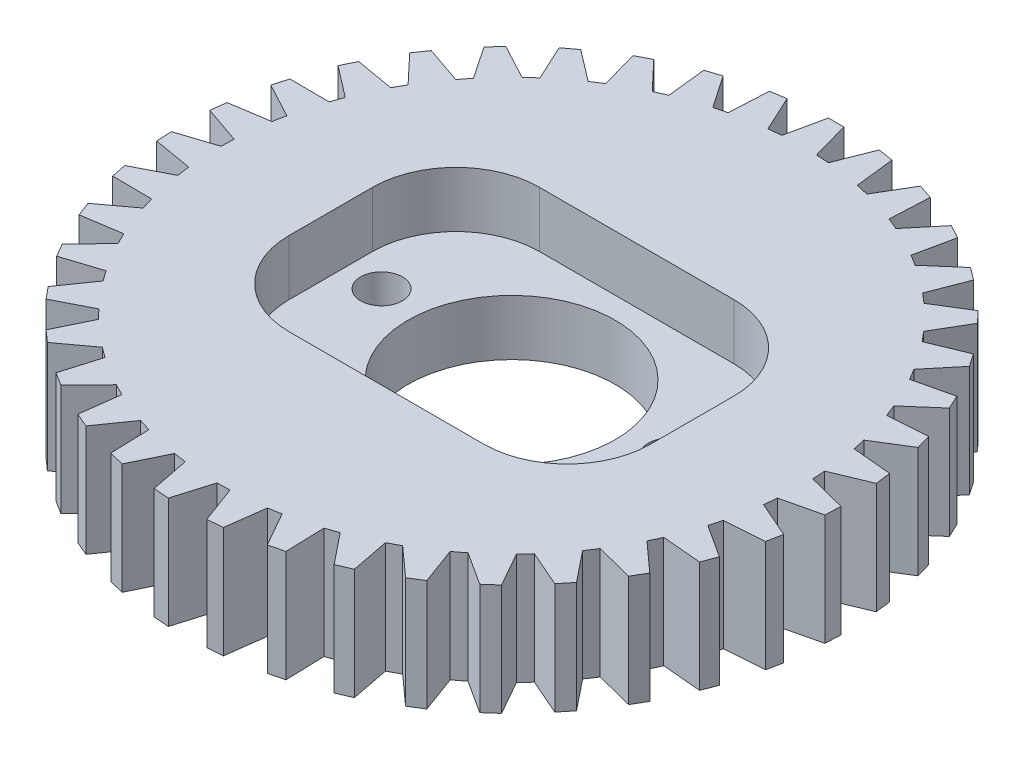
SolidWorks part; units mm, degrees
ref_plane "Front Plane" through (0, 0, 0) normal (0, 0, 1) x (1, 0, 0)
ref_plane "Top Plane" through (0, 0, 0) normal (0, 1, 0) x (1, 0, 0)
ref_plane "Right Plane" through (0, 0, 0) normal (1, 0, 0) x (0, 0, -1)
sketch "Sketch2" plane through (0, 0, 0) normal (0, 1, 0) x (1, 0, 0)
  line L0 (0, 10.5) -> (0, -22.3339) construction
  line L1 (10.5, 0) -> (-25.2541, 0) construction
  circle A0 centre (0, 0) radius 10.5
  dimension "D1" = 21
extrude "Boss-Extrude1" add sketch "Sketch2" along normal blind 4
sketch "Sketch3" plane through (0, 4, 0) normal (0, 1, 0) x (1, 0, 0)
  line L1 (-6.5, 4.5) -> (6.5, 4.5)
  line L2 (-6.5, 4.5) -> (-6.5, -4.5)
  line L3 (-6.5, -4.5) -> (6.5, -4.5)
  line L4 (6.5, 4.5) -> (6.5, -4.5)
  line L5 (-6.5, 4.5) -> (6.5, -4.5) construction
  line L6 (-6.5, -4.5) -> (6.5, 4.5) construction
  point P0 (0, 0)
  dimension "D1" = 13
  dimension "D2" = 9
extrude "Cut-Extrude1" cut sketch "Sketch3" against normal blind 2
fillet "Fillet1" radius 3 4 edges at (-6.5, 3, 4.5) (6.5, 3, 4.5) (-6.5, 3, -4.5) (6.5, 3, -4.5)
sketch "Sketch4" plane through (0, 2, 0) normal (0, 1, 0) x (1, 0, 0)
  line L1 (3.5, 4.5) -> (-3.5, 4.5) construction
  line L2 (0, 0) -> (0, -17.7909) construction
  circle A0 centre (0, 0) radius 3.725
  circle A2 centre (-5.1761, 0.4977) radius 0.75
  circle A3 centre (5.1761, 0.4977) radius 0.75
  dimension "D1" = 7.45
  dimension "D2" = 5.2
  dimension "D3" = 4.5
extrude "Cut-Extrude2" cut sketch "Sketch4" against normal through all
sketch "Sketch5" plane through (0, 4, 0) normal (0, 1, 0) x (1, 0, 0)
  line L0 (-0.7576, 10.4726) -> (-0.4614, 11.8538)
  line L1 (-0.4614, 11.8538) -> (0.0939, 11.8538)
  line L2 (0.0939, 11.8538) -> (0.4777, 10.4891)
  line L3 (1.9941, 11.6853) -> (2.1541, 10.2767)
  line L4 (1.446, 11.7743) -> (1.9941, 11.6853)
  line L5 (0.9321, 10.4585) -> (1.446, 11.7743)
  line L6 (3.8428, 11.2141) -> (3.7747, 9.798)
  line L7 (3.3161, 11.3899) -> (3.8428, 11.2141)
  line L8 (2.5977, 10.1736) -> (3.3161, 11.3899)
  line L9 (5.5919, 10.4524) -> (5.2976, 9.0656)
  line L10 (5.1002, 10.7105) -> (5.5919, 10.4524)
  line L11 (4.196, 9.6251) -> (5.1002, 10.7105)
  line L12 (7.1961, 9.4201) -> (6.6832, 8.0985)
  line L13 (6.7522, 9.7536) -> (7.1961, 9.4201)
  line L14 (5.6857, 8.8274) -> (6.7522, 9.7536)
  line L15 (8.614, 8.1437) -> (7.8957, 6.9215)
  line L16 (8.2294, 8.5442) -> (8.614, 8.1437)
  line L17 (7.0281, 7.801) -> (8.2294, 8.5442)
  line L18 (9.8088, 6.6565) -> (8.9038, 5.5653)
  line L19 (9.4934, 7.1135) -> (9.8088, 6.6565)
  line L20 (8.1884, 6.5726) -> (9.4934, 7.1135)
  line L21 (10.7496, 4.9968) -> (9.6812, 4.065)
  line L22 (10.5115, 5.4985) -> (10.7496, 4.9968)
  line L23 (9.1367, 5.174) -> (10.5115, 5.4985)
  line L24 (11.4119, 3.2078) -> (10.2079, 2.4594)
  line L25 (11.2574, 3.7411) -> (11.4119, 3.2078)
  line L26 (9.8484, 3.6414) -> (11.2574, 3.7411)
  line L27 (11.7787, 1.3356) -> (10.4702, 0.7901)
  line L28 (11.7118, 1.8869) -> (11.7787, 1.3356)
  line L29 (10.305, 2.0144) -> (11.7118, 1.8869)
  line L30 (11.8404, -0.5711) -> (10.4614, -0.8997)
  line L31 (11.8628, -0.0163) -> (11.8404, -0.5711)
  line L32 (10.4946, 0.3353) -> (11.8628, -0.0163)
  line L33 (11.5955, -2.463) -> (10.1816, -2.5662)
  line L34 (11.7066, -1.919) -> (11.5955, -2.463)
  line L35 (10.4125, -1.3525) -> (11.7066, -1.919)
  line L36 (11.0502, -4.2912) -> (9.6381, -4.1662)
  line L37 (11.2471, -3.772) -> (11.0502, -4.2912)
  line L38 (10.0607, -3.0053) -> (11.2471, -3.772)
  line L39 (10.2188, -6.0082) -> (8.845, -5.6583)
  line L40 (10.4964, -5.5273) -> (10.2188, -6.0082)
  line L41 (9.4484, -4.5802) -> (10.4964, -5.5273)
  line L42 (9.1227, -7.5696) -> (7.8228, -7.0039)
  line L43 (9.4738, -7.1395) -> (9.1227, -7.5696)
  line L44 (8.5913, -6.0365) -> (9.4738, -7.1395)
  line L45 (7.7903, -8.935) -> (6.598, -8.168)
  line L46 (8.2059, -8.5667) -> (7.7903, -8.935)
  line L47 (7.5117, -7.3365) -> (8.2059, -8.5667)
  line L48 (6.2561, -10.0689) -> (5.2023, -9.1206)
  line L49 (6.7254, -9.7721) -> (6.2561, -10.0689)
  line L50 (6.2376, -8.4464) -> (6.7254, -9.7721)
  line L51 (4.5599, -10.9421) -> (3.6719, -9.837)
  line L52 (5.0708, -10.7244) -> (4.5599, -10.9421)
  line L53 (4.8019, -9.3376) -> (5.0708, -10.7244)
  line L54 (2.7457, -11.5318) -> (2.0464, -10.2987)
  line L55 (3.2848, -11.3989) -> (2.7457, -11.5318)
  line L56 (3.2419, -9.987) -> (3.2848, -11.3989)
  line L57 (0.8603, -11.8229) -> (0.3678, -10.4936)
  line L58 (1.4138, -11.7782) -> (0.8603, -11.8229)
  line L59 (1.5979, -10.3777) -> (1.4138, -11.7782)
  line L60 (-1.0474, -11.8078) -> (-1.3202, -10.4167)
  line L61 (-0.4939, -11.8525) -> (-1.0474, -11.8078)
  line L62 (-0.0875, -10.4996) -> (-0.4939, -11.8525)
  line L63 (-2.9279, -11.4869) -> (-2.9741, -10.07)
  line L64 (-2.3888, -11.6198) -> (-2.9279, -11.4869)
  line L65 (-1.7707, -10.3496) -> (-2.3888, -11.6198)
  line L66 (-4.7327, -10.8685) -> (-4.5509, -9.4625)
  line L67 (-4.2218, -11.0861) -> (-4.7327, -10.8685)
  line L68 (-3.4079, -9.9316) -> (-4.2218, -11.0861)
  line L69 (-6.4148, -9.9686) -> (-6.0099, -8.61)
  line L70 (-5.9455, -10.2653) -> (-6.4148, -9.9686)
  line L71 (-4.9569, -9.2563) -> (-5.9455, -10.2653)
  line L72 (-7.9308, -8.8105) -> (-7.3132, -7.5344)
  line L73 (-7.5152, -9.1787) -> (-7.9308, -8.8105)
  line L74 (-6.3775, -8.3413) -> (-7.5152, -9.1787)
  line L75 (-9.2414, -7.4242) -> (-8.4271, -6.2637)
  line L76 (-8.8902, -7.8543) -> (-9.2414, -7.4242)
  line L77 (-7.633, -7.2102) -> (-8.8902, -7.8543)
  line L78 (-10.3126, -5.8456) -> (-9.3227, -4.8308)
  line L79 (-10.035, -6.3265) -> (-10.3126, -5.8456)
  line L80 (-8.6908, -5.8924) -> (-10.035, -6.3265)
  line L81 (-11.1168, -4.1157) -> (-9.9769, -3.2728)
  line L82 (-10.9199, -4.6349) -> (-11.1168, -4.1157)
  line L83 (-9.5234, -4.422) -> (-10.9199, -4.6349)
  line L84 (-11.633, -2.2791) -> (-10.3727, -1.63)
  line L85 (-11.522, -2.8232) -> (-11.633, -2.2791)
  line L86 (-10.1094, -2.8371) -> (-11.522, -2.8232)
  line L87 (-11.848, -0.3835) -> (-10.4999, 0.055)
  line L88 (-11.8256, -0.9383) -> (-11.848, -0.3835)
  line L89 (-10.4336, -1.1787) -> (-11.8256, -0.9383)
  line L90 (-11.7561, 1.522) -> (-10.3551, 1.7386)
  line L91 (-11.823, 0.9708) -> (-11.7561, 1.522)
  line L92 (-10.4876, 0.5102) -> (-11.823, 0.9708)
  line L93 (-11.3597, 3.3881) -> (-9.9421, 3.3771)
  line L94 (-11.5142, 2.8547) -> (-11.3597, 3.3881)
  line L95 (-10.2699, 2.186) -> (-11.5142, 2.8547)
  line L96 (-10.6691, 5.1664) -> (-9.2716, 4.9282)
  line L97 (-10.9071, 4.6648) -> (-10.6691, 5.1664)
  line L98 (-9.7863, 3.8051) -> (-10.9071, 4.6648)
  line L99 (-9.7022, 6.811) -> (-8.361, 6.3517)
  line L100 (-10.0176, 6.354) -> (-9.7022, 6.811)
  line L101 (-9.0492, 5.3256) -> (-10.0176, 6.354)
  line L102 (-8.484, 8.2791) -> (-7.2338, 7.6106)
  line L103 (-8.8686, 7.8787) -> (-8.484, 8.2791)
  line L104 (-8.0777, 6.7082) -> (-8.8686, 7.8787)
  line L105 (-7.0461, 9.5328) -> (-5.9193, 8.6725)
  line L106 (-7.49, 9.1993) -> (-7.0461, 9.5328)
  line L107 (-6.897, 7.9171) -> (-7.49, 9.1993)
  line L108 (-5.4256, 10.5397) -> (-4.4515, 9.5097)
  line L109 (-5.9173, 10.2816) -> (-5.4256, 10.5397)
  line L110 (-5.5377, 8.921) -> (-5.9173, 10.2816)
  line L111 (-3.6647, 11.2735) -> (-2.8684, 10.1006)
  line L112 (-4.1914, 11.0977) -> (-3.6647, 11.2735)
  line L113 (-4.035, 9.6938) -> (-4.1914, 11.0977)
  line L114 (-1.8088, 11.7154) -> (-1.211, 10.4299)
  line L115 (-2.3569, 11.6263) -> (-1.8088, 11.7154)
  line L116 (-2.4277, 10.2155) -> (-2.3569, 11.6263)
  circle A0 centre (0, 0) radius 10.5 construction
  arc A1 (-0.7576, 10.4726) -> (0.4777, 10.4891) centre (0, 0) cw
  arc A2 (0.9321, 10.4585) -> (2.1541, 10.2767) centre (0, 0) cw
  arc A3 (2.5977, 10.1736) -> (3.7747, 9.798) centre (0, 0) cw
  arc A4 (4.196, 9.6251) -> (5.2976, 9.0656) centre (0, 0) cw
  arc A5 (5.6857, 8.8274) -> (6.6832, 8.0985) centre (0, 0) cw
  arc A6 (7.0281, 7.801) -> (7.8957, 6.9215) centre (0, 0) cw
  arc A7 (8.1884, 6.5726) -> (8.9038, 5.5653) centre (0, 0) cw
  arc A8 (9.1367, 5.174) -> (9.6812, 4.065) centre (0, 0) cw
  arc A9 (9.8484, 3.6414) -> (10.2079, 2.4594) centre (0, 0) cw
  arc A10 (10.305, 2.0144) -> (10.4702, 0.7901) centre (0, 0) cw
  arc A11 (10.4946, 0.3353) -> (10.4614, -0.8997) centre (0, 0) cw
  arc A12 (10.4125, -1.3525) -> (10.1816, -2.5662) centre (0, 0) cw
  arc A13 (10.0607, -3.0053) -> (9.6381, -4.1662) centre (0, 0) cw
  arc A14 (9.4484, -4.5802) -> (8.845, -5.6583) centre (0, 0) cw
  arc A15 (8.5913, -6.0365) -> (7.8228, -7.0039) centre (0, 0) cw
  arc A16 (7.5117, -7.3365) -> (6.598, -8.168) centre (0, 0) cw
  arc A17 (6.2376, -8.4464) -> (5.2023, -9.1206) centre (0, 0) cw
  arc A18 (4.8019, -9.3376) -> (3.6719, -9.837) centre (0, 0) cw
  arc A19 (3.2419, -9.987) -> (2.0464, -10.2987) centre (0, 0) cw
  arc A20 (1.5979, -10.3777) -> (0.3678, -10.4936) centre (0, 0) cw
  arc A21 (-0.0875, -10.4996) -> (-1.3202, -10.4167) centre (0, 0) cw
  arc A22 (-1.7707, -10.3496) -> (-2.9741, -10.07) centre (0, 0) cw
  arc A23 (-3.4079, -9.9316) -> (-4.5509, -9.4625) centre (0, 0) cw
  arc A24 (-4.9569, -9.2563) -> (-6.0099, -8.61) centre (0, 0) cw
  arc A25 (-6.3775, -8.3413) -> (-7.3132, -7.5344) centre (0, 0) cw
  arc A26 (-7.633, -7.2102) -> (-8.4271, -6.2637) centre (0, 0) cw
  arc A27 (-8.6908, -5.8924) -> (-9.3227, -4.8308) centre (0, 0) cw
  arc A28 (-9.5234, -4.422) -> (-9.9769, -3.2728) centre (0, 0) cw
  arc A29 (-10.1094, -2.8371) -> (-10.3727, -1.63) centre (0, 0) cw
  arc A30 (-10.4336, -1.1787) -> (-10.4999, 0.055) centre (0, 0) cw
  arc A31 (-10.4876, 0.5102) -> (-10.3551, 1.7386) centre (0, 0) cw
  arc A32 (-10.2699, 2.186) -> (-9.9421, 3.3771) centre (0, 0) cw
  arc A33 (-9.7863, 3.8051) -> (-9.2716, 4.9282) centre (0, 0) cw
  arc A34 (-9.0492, 5.3256) -> (-8.361, 6.3517) centre (0, 0) cw
  arc A35 (-8.0777, 6.7082) -> (-7.2338, 7.6106) centre (0, 0) cw
  arc A36 (-6.897, 7.9171) -> (-5.9193, 8.6725) centre (0, 0) cw
  arc A37 (-5.5377, 8.921) -> (-4.4515, 9.5097) centre (0, 0) cw
  arc A38 (-4.035, 9.6938) -> (-2.8684, 10.1006) centre (0, 0) cw
  arc A39 (-2.4277, 10.2155) -> (-1.211, 10.4299) centre (0, 0) cw
  point P149 (0, 0)
  dimension "D1" = 39
extrude "Boss-Extrude2" add sketch "Sketch5" against normal blind 4
